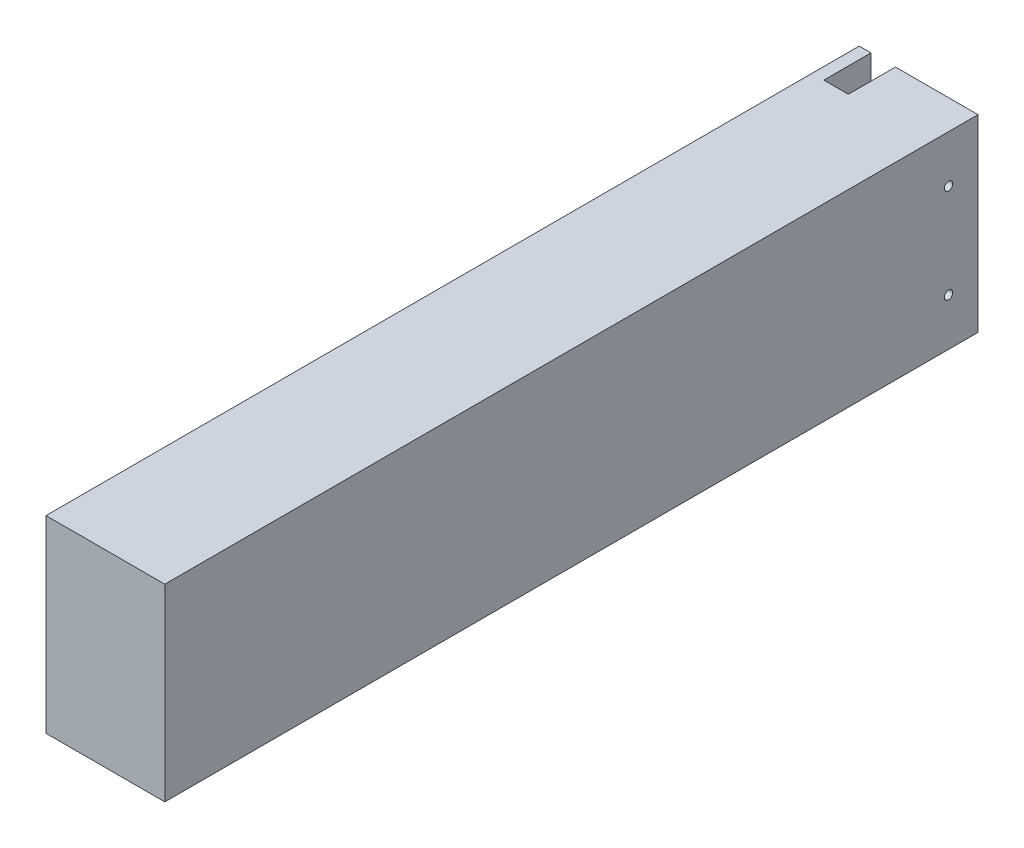
SolidWorks part; units mm, degrees
ref_plane "Front Plane" through (0, 0, 0) normal (0, 0, 1) x (1, 0, 0)
ref_plane "Top Plane" through (0, 0, 0) normal (0, 1, 0) x (1, 0, 0)
ref_plane "Right Plane" through (0, 0, 0) normal (1, 0, 0) x (0, 0, -1)
sketch "Sketch2" plane through (0, 0, 0) normal (0, 1, 0) x (1, 0, 0)
  line L0 (0, 0) -> (0, 15.875)
  line L1 (0, 15.875) -> (3.175, 15.875)
  line L2 (3.175, 15.875) -> (3.175, 3.175)
  line L3 (12.954, 0) -> (12.954, 15.875)
  line L4 (12.954, 15.875) -> (9.779, 15.875)
  line L5 (12.954, 0) -> (0, 0)
  line L6 (9.779, 15.875) -> (9.779, 3.175)
  line L7 (9.779, 3.175) -> (3.175, 3.175)
  line L8 (6.477, 3.175) -> (6.477, 0) construction
  dimension "D1" = 6.604
  dimension "D2" = 3.175
  dimension "D3" = 12.7
extrude "Boss-Extrude1" add sketch "Sketch2" along normal blind 50.8
sketch "Sketch5" plane through (12.954, 0, 0) normal (1, 0, 0) x (0, 0, -1)
  line L4 (0, 0) -> (15.875, 0)
  line L5 (15.875, 0) -> (15.875, 50.8)
  line L6 (15.875, 50.8) -> (0, 50.8)
  line L7 (0, 50.8) -> (0, 0)
  line L8 (0, 0) -> (15.875, 0)
  line L9 (15.875, 0) -> (15.875, 50.8)
  line L10 (15.875, 50.8) -> (0, 50.8)
  line L11 (0, 50.8) -> (0, 0)
  dimension "D1" = 0
extrude "Boss-Extrude2" add sketch "Sketch5" along normal blind 19.05
hole_wizard "#4-40 Tapped Hole1" positions "Sketch7" profile "Sketch6" tap size "#4-40" standard "Ansi Inch"
sketch "Sketch7" plane through (32.004, 0, 0) normal (1, 0, 0) x (0, 0, -1)
  line L0 (0, 25.4) -> (15.875, 25.4) construction
  line L1 (0, 50.8) -> (0, 0) construction
  line L2 (15.875, 0) -> (15.875, 50.8) construction
  line L4 (7.9375, 25.4) -> (7.9375, 0) construction
  line L5 (0, 0) -> (15.875, 0) construction
  point P0 (7.9375, 12.7)
  point P17 (7.9375, 38.1)
sketch "Sketch6" plane through (32.004, 12.7, -7.9375) normal (0, 1, 0) x (0, 0, -1)
  line L0 (0, 0) -> (0, 22.9032)
  line L1 (0, 22.9032) -> (1.1303, 22.224)
  line L2 (1.1303, 22.224) -> (1.1303, 0)
  line L5 (1.1303, 0) -> (0, 0)
  line L10 (0, 22.9032) -> (-1.1303, 22.224) construction
  line L11 (0, -6.35) -> (0, 107.95) construction
  dimension "Tap Drill Dia." = 2.2606
  dimension "Tap Drill Depth" = 22.224
  dimension "Drill Angle" = 118
cosmetic thread "Hole Thread1" parameters "D1"=5.6896, "D2"=2.8448
cosmetic thread "Hole Thread2" parameters "D1"=5.6896, "D2"=2.8448
sketch "Sketch9" plane through (0, 0, 0) normal (0, 0, 1) x (1, 0, 0)
  line L8 (0, 0) -> (32.004, 0)
  line L9 (32.004, 0) -> (32.004, 50.8)
  line L10 (32.004, 50.8) -> (0, 50.8)
  line L11 (0, 50.8) -> (0, 0)
  line L12 (0, 0) -> (32.004, 0)
  line L13 (32.004, 0) -> (32.004, 50.8)
  line L14 (32.004, 50.8) -> (0, 50.8)
  line L15 (0, 50.8) -> (0, 0)
  dimension "D1" = 0
extrude "Boss-Extrude4" add sketch "Sketch9" along normal blind 203.2
sketch "Sketch8" plane through (0, 0, 0) normal (0, 0, 1) x (1, 0, 0)
  line L0 (0, 25.4) -> (32.004, 25.4) construction
  line L1 (0, 50.8) -> (0, 0) construction
  line L2 (32.004, 50.8) -> (32.004, 0) construction
  line L3 (0, 0) -> (32.004, 0) construction
  line L4 (0, 39.37) -> (32.004, 39.37)
  line L5 (0, 39.37) -> (0, 11.43) construction
  line L6 (0, 11.43) -> (32.004, 11.43)
  line L7 (32.004, 39.37) -> (32.004, 11.43) construction
  line L8 (0, 39.37) -> (32.004, 11.43) construction
  line L9 (0, 11.43) -> (32.004, 39.37) construction
  line L10 (0, 11.43) -> (0, 0)
  line L11 (0, 0) -> (32.004, 0)
  line L12 (32.004, 0) -> (32.004, 11.43)
  line L13 (0, 39.37) -> (0, 50.8)
  line L14 (0, 50.8) -> (32.004, 50.8)
  line L15 (32.004, 50.8) -> (32.004, 39.37)
  point P6 (16.002, 25.4)
  dimension "D1" = 11.43
